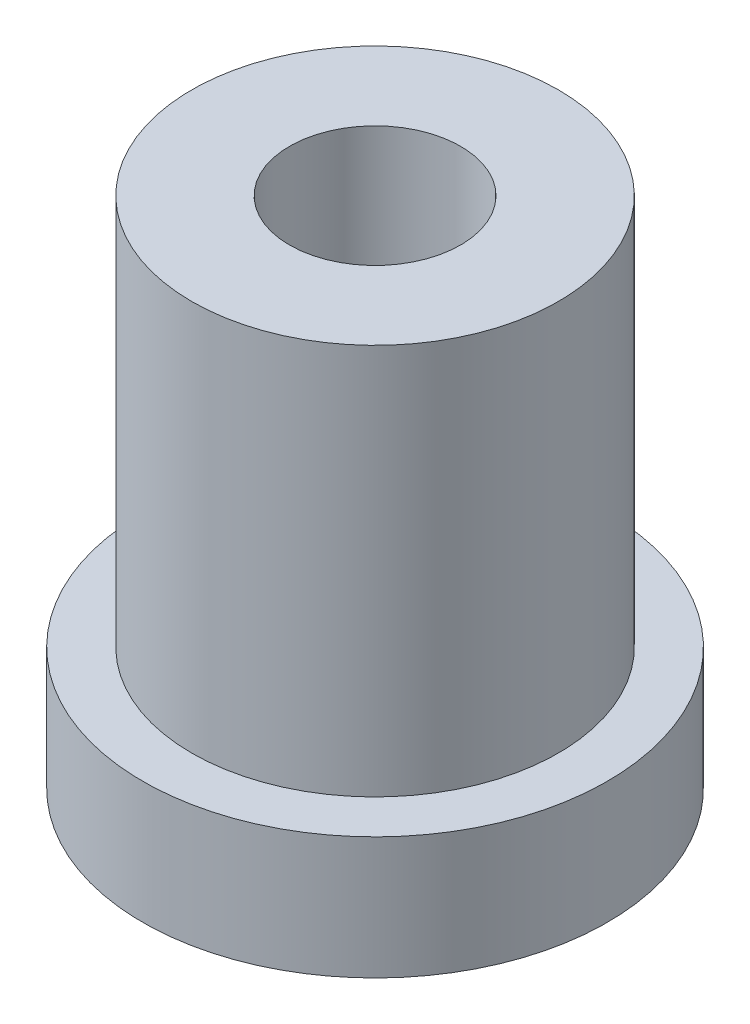
SolidWorks part; units mm, degrees
ref_plane "Front Plane" through (0, 0, 0) normal (0, 0, 1) x (1, 0, 0)
ref_plane "Top Plane" through (0, 0, 0) normal (0, 1, 0) x (1, 0, 0)
ref_plane "Right Plane" through (0, 0, 0) normal (1, 0, 0) x (0, 0, -1)
sketch "Sketch1" plane through (0, 0, 0) normal (0, 1, 0) x (1, 0, 0)
  circle A0 centre (0, 0) radius 3.75
  dimension "D1" = 7.5
extrude "Boss-Extrude1" add sketch "Sketch1" along normal blind 10.5
hole_wizard "Ø3.5 (3.5) Diameter Hole1" positions "Sketch2" profile "Sketch3" hole size "Ø3.5" standard "JIS" end condition through all
sketch "Sketch2" plane through (0, 10.5, 0) normal (0, 1, 0) x (1, 0, 0)
  point P0 (0, 0)
sketch "Sketch3" plane through (0, 10.5, 0) normal (1, 0, 0) x (0, 0, 1)
  line L0 (0, 0) -> (0, 10.5)
  line L1 (0, 10.5) -> (1.75, 10.5)
  line L2 (1.75, 10.5) -> (1.75, 0)
  line L5 (1.75, 0) -> (0, 0)
  line L11 (0, -6.35) -> (0, 107.95) construction
  dimension "Thru Hole Dia." = 3.5
  dimension "Thru Hole Depth" = 10.5
sketch "Sketch5" plane through (0, 0, 0) normal (0, -1, 0) x (1, 0, 0)
  circle A0 centre (0, 0) radius 3.75 construction
  circle A1 centre (0, 0) radius 3.75
  circle A2 centre (0, 0) radius 4.75
  dimension "D1" = 9.5
extrude "Boss-Extrude2" add sketch "Sketch5" against normal blind 2.5
